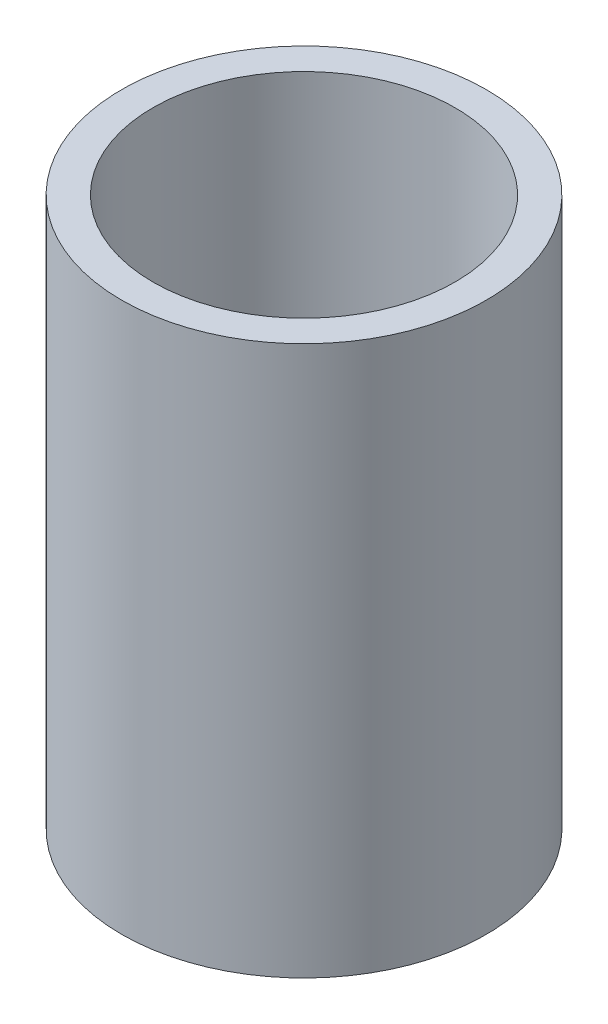
SolidWorks part; units mm, degrees
material "6061 Alloy"
ref_plane "Front Plane" through (0, 0, 0) normal (0, 0, 1) x (1, 0, 0)
ref_plane "Top Plane" through (0, 0, 0) normal (0, 1, 0) x (1, 0, 0)
ref_plane "Right Plane" through (0, 0, 0) normal (1, 0, 0) x (0, 0, -1)
sketch "Sketch1" plane through (0, 0, 0) normal (0, 1, 0) x (1, 0, 0)
  circle A0 centre (0, 0) radius 17.4625
  circle A1 centre (0, 0) radius 21.082
  dimension "D1" = 42.164
  dimension "D2" = 34.925
extrude "Boss-Extrude1" add sketch "Sketch1" along normal blind 63.5
